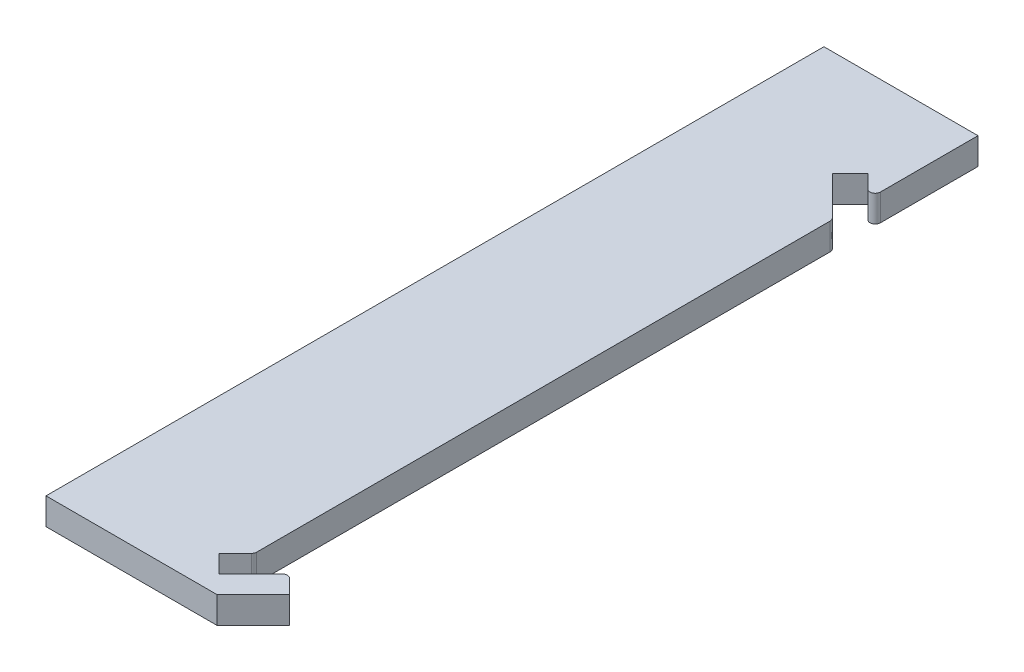
SolidWorks part; units mm, degrees
ref_plane "Front Plane" through (0, 0, 0) normal (0, 0, 1) x (1, 0, 0)
ref_plane "Top Plane" through (0, 0, 0) normal (0, 1, 0) x (1, 0, 0)
ref_plane "Right Plane" through (0, 0, 0) normal (1, 0, 0) x (0, 0, -1)
sketch "Sketch1" plane through (0, 0, 0) normal (0, 1, 0) x (1, 0, 0)
  line L1 (0, 0) -> (30, 0)
  line L2 (0, 0) -> (0, 160)
  line L3 (0, 160) -> (30, 160)
  line L4 (30, 0) -> (30, 160)
  dimension "D1" = 30
  dimension "D2" = 160
extrude "Boss-Extrude1" add sketch "Sketch1" along normal blind 5.2
sketch "Sketch2" plane through (0, 5.2, 0) normal (0, 1, 0) x (1, 0, 0)
  line L0 (30, 131.6421) -> (22.2218, 139.4203)
  line L5 (30, 19.1421) -> (19.3934, 8.5355)
  line L10 (30, 0) -> (30, 160) construction
  line L13 (19.3934, 8.5355) -> (0, 8.5355)
  line L14 (22.2218, 139.4203) -> (25.6866, 142.8851)
  line L16 (0, 8.5355) -> (0, 0)
  line L17 (0, 0) -> (30, 0)
  line L18 (30, 0) -> (30, 19.1421)
  line L19 (25.6866, 142.8851) -> (30, 138.5718)
  line L20 (30, 138.5718) -> (30, 131.6421)
  dimension "D5" = 11
  dimension "D6" = 112.5
  dimension "D1" = 15
  dimension "D2" = 45
  dimension "D3" = 28.3579
  dimension "D4" = 4.9
  dimension "D7" = 4.3134
extrude "Cut-Extrude1" cut sketch "Sketch2" against normal blind 10
fillet "Fillet1" radius 1 2 edges at (30, 2.6, -131.6421) (30, 2.6, -138.5718)
sketch "Sketch3" plane through (0, 5.2, 0) normal (0, 1, 0) x (1, 0, 0)
  line L1 (30, 19.1421) -> (19.3934, 8.5355) construction
  line L2 (26.5352, 15.6773) -> (30, 12.2125)
  line L3 (33.2527, 8.5355) -> (40.3238, 15.6066)
  line L4 (40.3238, 15.6066) -> (36.8589, 19.0714)
  line L5 (36.8589, 19.0714) -> (30, 12.2125)
  line L6 (19.3934, 8.5355) -> (33.2527, 8.5355)
  line L7 (26.5352, 15.6773) -> (19.3934, 8.5355)
  dimension "D2" = 4.9
  dimension "D3" = 10
  dimension "D1" = 4.9
extrude "Boss-Extrude2" add sketch "Sketch3" against normal blind 5.2
fillet "Fillet2" radius 1 2 edges at (36.8589, 2.6, -19.0714) (30, 2.6, -19.1421)
equation "\"thick\"= 5.2'board thickness"
equation "\"fit\"= 0.3mm'fit adjustment"
equation "\"depth\"= \"thick\" * 1.5'cut depth"
equation "\"chamfer\"= \"thick\" / 2'fillet radius"
equation "\"width\"= \"thick\" - \"fit\"'cut width"
equation "\"gap\"= \"depth\" * 2'cut gap"
equation "\"curv\"= \"gap\" * 2'curvature radius"
equation "\"D1@Boss-Extrude1\"=\"thick\""
equation "\"D4@Sketch2\"=\"width\""
equation "\"D2@Sketch3\"=\"width\""
equation "\"D1@Boss-Extrude2\"=\"thick\""
